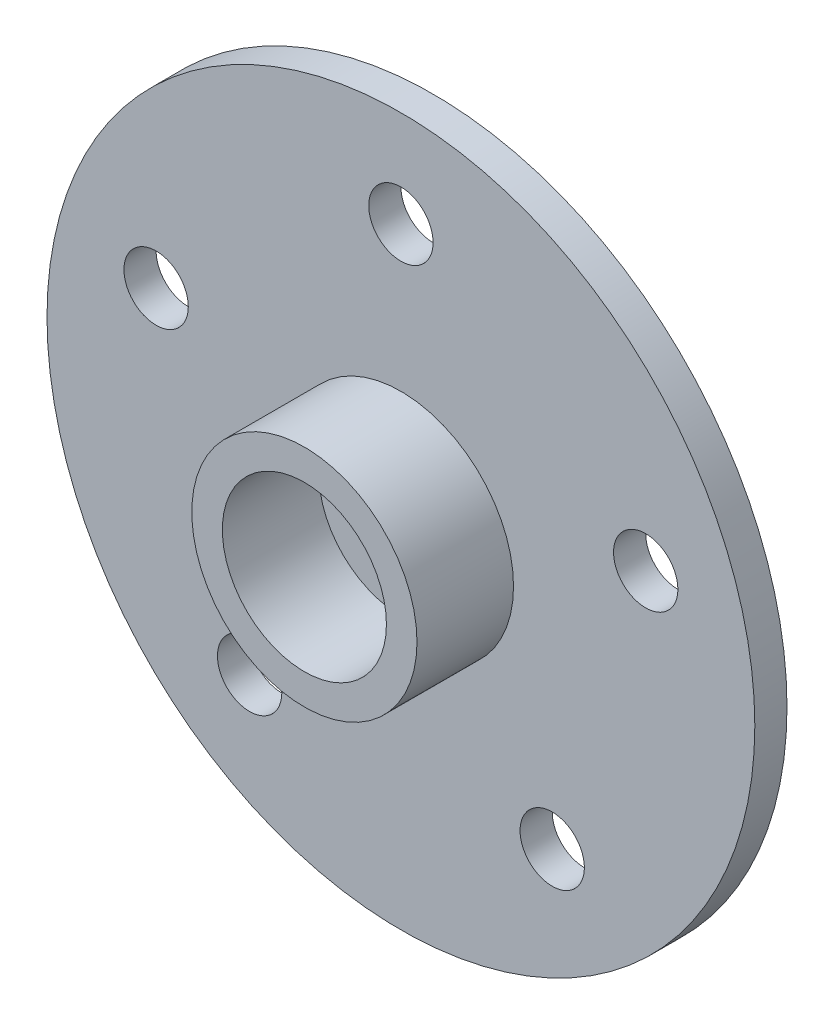
SolidWorks part; units mm, degrees
ref_plane "前视基准面" through (0, 0, 0) normal (0, 0, 1) x (1, 0, 0)
ref_plane "上视基准面" through (0, 0, 0) normal (0, 1, 0) x (1, 0, 0)
ref_plane "右视基准面" through (0, 0, 0) normal (1, 0, 0) x (0, 0, -1)
other "Configuration Table"
sketch "草图1" plane through (0, 0, 0) normal (0, 0, 1) x (1, 0, 0)
  circle A4 centre (0, 0) radius 3.15
  circle A5 centre (0, 0) radius 22
  circle A6 centre (0, 0) radius 16 construction
  circle A8 centre (0, 16) radius 2
  circle A9 centre (15.2169, 4.9443) radius 2
  circle A10 centre (9.4046, -12.9443) radius 2
  circle A11 centre (-9.4046, -12.9443) radius 2
  circle A12 centre (-15.2169, 4.9443) radius 2
  point P0 (0, 0)
  point P17 (0, 0)
  point P19 (0, 0)
  dimension "D3" = 5
  dimension "D5" = 4
  dimension "D1" = 44
  dimension "D2" = 32
  dimension "D4" = 6.3
extrude "凸台-拉伸1" add sketch "草图1" along normal blind 2
sketch "草图2" plane through (0, 0, 2) normal (0, 0, 1) x (1, 0, 0)
  circle A0 centre (0, 0) radius 7
  circle A1 centre (0, 0) radius 5.1
  dimension "D1" = 14
  dimension "D2" = 10.2
extrude "凸台-拉伸3" add sketch "草图2" along normal blind 6
